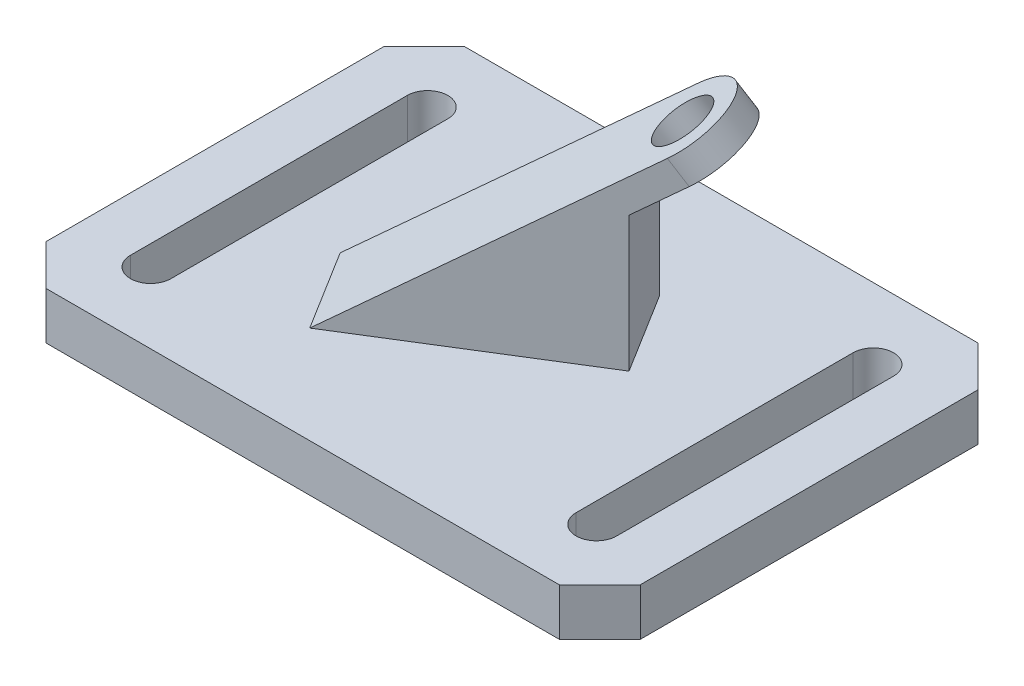
SolidWorks part; units mm, degrees
ref_plane "Front Plane" through (0, 0, 0) normal (0, 0, 1) x (1, 0, 0)
ref_plane "Top Plane" through (0, 0, 0) normal (0, 1, 0) x (1, 0, 0)
ref_plane "Right Plane" through (0, 0, 0) normal (1, 0, 0) x (0, 0, -1)
sketch "Sketch1" plane through (0, 0, 0) normal (0, 1, 0) x (1, 0, 0)
  line L0 (33, 20.5) -> (33, -20.5) construction
  line L1 (-38, -31) -> (38, -31)
  line L2 (-44, -25) -> (-44, 25)
  line L3 (-38, 31) -> (38, 31)
  line L4 (44, -25) -> (44, 25)
  line L5 (-44, -31) -> (44, 31) construction
  line L6 (-44, 31) -> (44, -31) construction
  line L7 (36, 20.5) -> (36, -20.5)
  line L8 (30, 20.5) -> (30, -20.5)
  line L9 (0, 6.9892) -> (0, -8.2571) construction
  line L10 (-33, 20.5) -> (-33, -20.5) construction
  line L13 (38, 31) -> (44, 25)
  line L14 (38, -31) -> (44, -25)
  line L15 (-36, 20.5) -> (-36, -20.5)
  line L16 (-30, 20.5) -> (-30, -20.5)
  line L17 (-38, -31) -> (-44, -25)
  line L18 (-38, 31) -> (-44, 25)
  line L19 (-44, -25) -> (-44, 25)
  line L20 (-33, -20.5) -> (33, 20.5) construction
  arc A0 (36, 20.5) -> (30, 20.5) centre (33, 20.5) ccw
  arc A1 (30, -20.5) -> (36, -20.5) centre (33, -20.5) ccw
  arc A4 (-36, 20.5) -> (-30, 20.5) centre (-33, 20.5) cw
  arc A5 (-30, -20.5) -> (-36, -20.5) centre (-33, -20.5) cw
  point P0 (0, 0)
  point P8 (33, 0)
  point P17 (-33, 0)
  dimension "D1" = 62
  dimension "D2" = 41
  dimension "D3" = 10.5
  dimension "D4" = 6
  dimension "D5" = 8
  dimension "D6" = 88
  dimension "D7" = 6
  dimension "D8" = 45
  dimension "D9" = 6
  dimension "D10" = 45
extrude "Boss-Extrude2" add sketch "Sketch1" along normal blind 7 contours L3 L18 L2 L17 L1 L14 L4 L13 A1 L8 A0 L7 L16 A5 L15 A4
ref_plane "Plane1" through (0, 0, 0) normal (0.5277, 0, 0.8494) x (0.8494, 0, -0.5277)
sketch "Sketch4" plane through (0, 0, 0) normal (0.5277, 0, 0.8494) x (0.8494, 0, -0.5277)
  line L0 (-20.1141, 7) -> (24.8119, 39.6406)
  line L1 (-48.6369, 7) -> (15.9206, 7) construction
  line L2 (24.8119, 39.6406) -> (27.163, 36.4046)
  line L3 (27.163, 36.4046) -> (14.2188, 27)
  line L4 (14.2188, 27) -> (14.2188, 7)
  line L5 (14.2188, 7) -> (-20.1141, 7)
  dimension "D1" = 20
  dimension "D2" = 4
  dimension "D3" = 20
  dimension "D4" = 36
  dimension "D5" = 16
extrude "Boss-Extrude3" add sketch "Sketch4" along normal mid plane 14
sketch "Sketch6" plane through (-8.7305, 14.1464, 5.4235) normal (-0.4993, 0.809, 0.3102) x (0.8664, 0.4662, 0.1787)
  line L2 (38.6648, 20.8636) -> (-5.38, -12.9567) construction
  line L5 (30.1384, 31.9677) -> (-13.9064, -1.8526) construction
  line L9 (25.9744, 11.1191) -> (17.448, 22.2232) construction
  circle A0 centre (28.0564, 21.5434) radius 4
  circle A1 centre (28.0564, 21.5434) radius 7
  point P11 (0, 0)
  line M3 (30.1384, 31.9677) -> (-13.9064, -1.8526)
  line M5 (-5.38, -12.9567) -> (38.6648, 20.8636)
  line M6 (38.6648, 20.8636) -> (30.1384, 31.9677)
  dimension "D1" = 8
  dimension "D2" = 8
extrude "Cut-Extrude1" cut sketch "Sketch6" against normal up to next and the other way through all contours A0 | A1 M5 M6 M3
